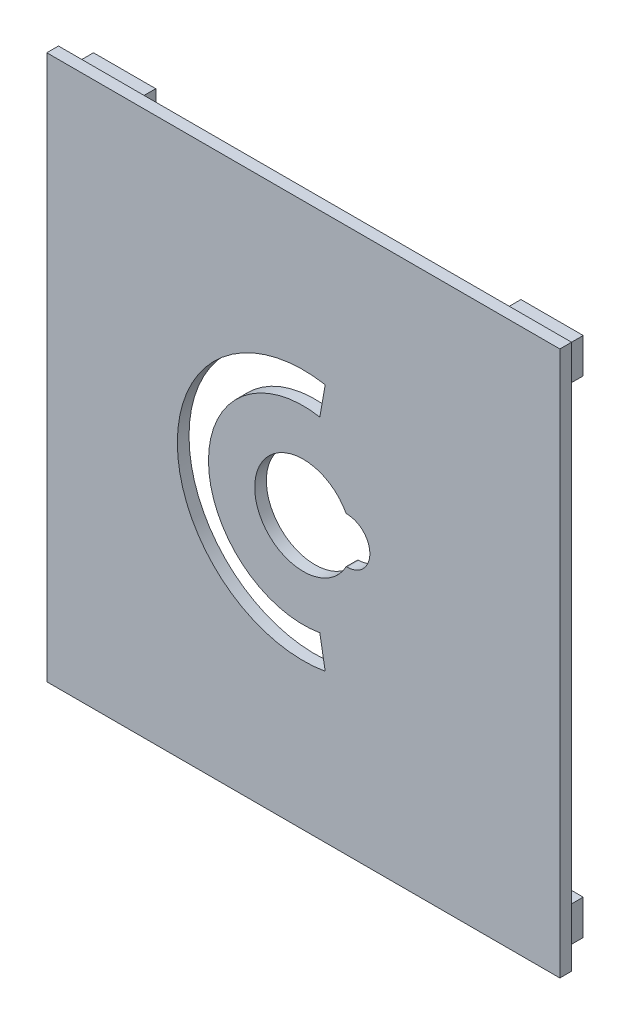
SolidWorks part; units mm, degrees
ref_plane "Front Plane" through (0, 0, 0) normal (0, 0, 1) x (1, 0, 0)
ref_plane "Top Plane" through (0, 0, 0) normal (0, 1, 0) x (1, 0, 0)
ref_plane "Right Plane" through (0, 0, 0) normal (1, 0, 0) x (0, 0, -1)
sketch "Sketch1" plane through (0, 0, 0) normal (0, 0, 1) x (1, 0, 0)
  line L0 (-10.75, -9.75) -> (121.1, -9.75) construction
  line L2 (121.1, -9.75) -> (55.175, -9.75)
  line L3 (121.1, -9.75) -> (121.1, 60.25)
  line L4 (121.1, 60.25) -> (55.175, 60.25)
  line L5 (55.175, -9.75) -> (55.175, 60.25)
  line L6 (-10.75, -9.75) -> (-10.75, 60.25) construction
  line L7 (-10.75, -9.75) -> (-10.75, 60.25) construction
  point P7 (0, 0)
  point P8 (55.175, -9.75)
  point P9 (0, 0)
  point P11 (0, 0)
extrude "Boss-Extrude1" add sketch "Sketch1" along normal blind 1.5 contours L5 L2 L3 L4
sketch "Sketch2" plane through (0, 0, 1.5) normal (0, 0, 1) x (1, 0, 0)
  line L4 (93.6475, 22.3) -> (93.7375, 22.3)
  line L5 (93.7375, 28.2) -> (93.6475, 28.2)
  line L6 (93.6475, 22.3) -> (93.7375, 22.3)
  line L7 (93.7375, 28.2) -> (93.6475, 28.2)
  arc A8 (93.7375, 22.3) -> (93.7375, 28.2) centre (93.7375, 25.25) ccw
  arc A9 (93.6475, 28.2) -> (93.6475, 22.3) centre (88.1375, 25.25) ccw
  arc A10 (93.7375, 22.3) -> (93.7375, 28.2) centre (93.7375, 25.25) ccw
  arc A11 (93.6475, 28.2) -> (93.6475, 22.3) centre (88.1375, 25.25) ccw
  dimension "D1" = 0.25
extrude "Cut-Extrude1" cut sketch "Sketch2" against normal up to next
ref_plane "Plane2" through (88.1375, 0, 0) normal (1, 0, 0) x (0, 0, -1)
ref_plane "Plane1" through (0, 25.25, 0) normal (0, 1, 0) x (1, 0, 0)
sketch "Sketch4" plane through (0, 0, 0) normal (0, 0, -1) x (-1, 0, 0)
  line L0 (-118.1, 57.25) -> (-118.1, 55.75)
  line L1 (-119.6, 58.75) -> (-111.6, 58.75)
  line L2 (-119.6, 58.75) -> (-119.6, 54.25)
  line L3 (-119.6, 54.25) -> (-111.6, 54.25)
  line L4 (-111.6, 58.75) -> (-111.6, 54.25)
  line L5 (-119.6, 58.75) -> (-119.6, 60.25) construction
  line L6 (-118.1, 55.75) -> (-113.1, 55.75)
  line L8 (-113.1, 57.25) -> (-113.1, 55.75)
  line L9 (-118.1, 57.25) -> (-113.1, 57.25)
  line L10 (-119.6, 58.75) -> (-121.1, 58.75) construction
  line L12 (-121.1, 60.25) -> (-55.175, 60.25) construction
  line L13 (-121.1, -9.75) -> (-121.1, 60.25) construction
  point P8 (-119.5596, 60.25)
  point P12 (-121.1, 58.75)
  dimension "D1" = 1.5
  dimension "D2" = 5
  dimension "D3" = 1.5
extrude "Boss-Extrude2" add sketch "Sketch4" along normal blind 3
mirror "Mirror1" about plane through (88.1375, 0, 0) normal (1, 0, 0) of "Boss-Extrude2"
mirror "Mirror2" about plane through (0, 25.25, 0) normal (0, 1, 0) of "Mirror1", "Boss-Extrude2"
sketch "Sketch3" [suppressed] plane through (121.1, 0, 0) normal (1, 0, 0) x (0, 0, -1)
  line L0 (0, -9.75) -> (0, 60.25) construction
  line L1 (-1.5, 60.25) -> (6, 60.25)
  line L2 (-1.5, 60.25) -> (-1.5, 61.75)
  line L3 (-1.5, 61.75) -> (6, 61.75)
  line L4 (6, 60.25) -> (6, 61.75)
  line L5 (6, 60.25) -> (4.5, 58.75)
  line L7 (4.5, 58.75) -> (4.5, 60.25)
  dimension "D1" = 1.5
  dimension "D2" = 6
  dimension "D3" = 45
sketch "Sketch5" plane through (0, 0, 1.5) normal (0, 0, 1) x (1, 0, 0)
  line L0 (90.254, 37.2535) -> (90.9486, 41.1927)
  line L1 (90.254, 13.2465) -> (90.9486, 9.3073)
  line L6 (80.2871, 33.1004) -> (76.4143, 32.0995)
  line L7 (76.4143, 32.0995) -> (77.165, 29.1949)
  line L8 (77.165, 29.1949) -> (82.7493, 30.6382)
  line L9 (82.7493, 30.6382) -> (84.1926, 36.2225)
  line L10 (84.1926, 36.2225) -> (81.288, 36.9732)
  line L11 (81.288, 36.9732) -> (80.2871, 33.1004)
  line L12 (80.2871, 33.1004) -> (76.4143, 32.0995) construction
  line L13 (76.4143, 32.0995) -> (77.165, 29.1949) construction
  line L14 (77.165, 29.1949) -> (82.7493, 30.6382) construction
  line L15 (82.7493, 30.6382) -> (84.1926, 36.2225) construction
  line L16 (84.1926, 36.2225) -> (81.288, 36.9732) construction
  line L17 (81.288, 36.9732) -> (80.2871, 33.1004) construction
  line L21 (77.2375, 30.5) -> (77.2375, 25.8)
  line L22 (77.2375, 25.8) -> (78.4349, 25.8)
  line L23 (78.4349, 24.7) -> (77.2375, 24.7)
  line L24 (77.2375, 24.7) -> (77.2375, 20)
  line L25 (78.0875, 19.15) -> (82.8875, 19.15)
  line L26 (82.0375, 20) -> (82.0375, 30.5)
  line L27 (82.8875, 31.35) -> (78.0875, 31.35)
  line L28 (77.2375, 30.5) -> (77.2375, 25.8) construction
  line L29 (77.2375, 25.8) -> (78.4349, 25.8) construction
  line L30 (78.4349, 24.7) -> (77.2375, 24.7) construction
  line L31 (77.2375, 24.7) -> (77.2375, 20) construction
  line L32 (78.0875, 19.15) -> (82.8875, 19.15) construction
  line L33 (82.0375, 20) -> (82.0375, 30.5) construction
  line L34 (82.8875, 31.35) -> (78.0875, 31.35) construction
  arc A0 (90.9486, 41.1927) -> (90.9486, 9.3073) centre (88.1375, 25.25) ccw
  circle A2 centre (88.1375, 25.25) radius 0.8 construction
  circle A3 centre (88.1375, 25.25) radius 0.8 construction
  arc A4 (90.254, 37.2535) -> (90.254, 13.2465) centre (88.1375, 25.25) ccw
  arc A10 (78.4349, 24.7) -> (78.4349, 25.8) centre (79.3875, 25.25) ccw
  arc A11 (77.2375, 20) -> (78.0875, 19.15) centre (78.0875, 20) ccw
  arc A12 (82.0375, 20) -> (82.8875, 19.15) centre (82.8875, 20) ccw
  arc A13 (82.8875, 31.35) -> (82.0375, 30.5) centre (82.8875, 30.5) ccw
  arc A14 (78.0875, 31.35) -> (77.2375, 30.5) centre (78.0875, 30.5) ccw
  arc A15 (78.4349, 24.7) -> (78.4349, 25.8) centre (79.3875, 25.25) ccw construction
  arc A16 (77.2375, 20) -> (78.0875, 19.15) centre (78.0875, 20) ccw construction
  arc A17 (82.0375, 20) -> (82.8875, 19.15) centre (82.8875, 20) ccw construction
  arc A18 (82.8875, 31.35) -> (82.0375, 30.5) centre (82.8875, 30.5) ccw construction
  arc A19 (78.0875, 31.35) -> (77.2375, 30.5) centre (78.0875, 30.5) ccw construction
  point P26 (0, 0)
  dimension "D2" = 4
  dimension "D4" = 200
  dimension "D1" = 0
  dimension "D3" = 0
extrude "Cut-Extrude2" cut sketch "Sketch5" against normal through all
equation "\"D1@Boss-Extrude2\"=1.50mm+.25"
